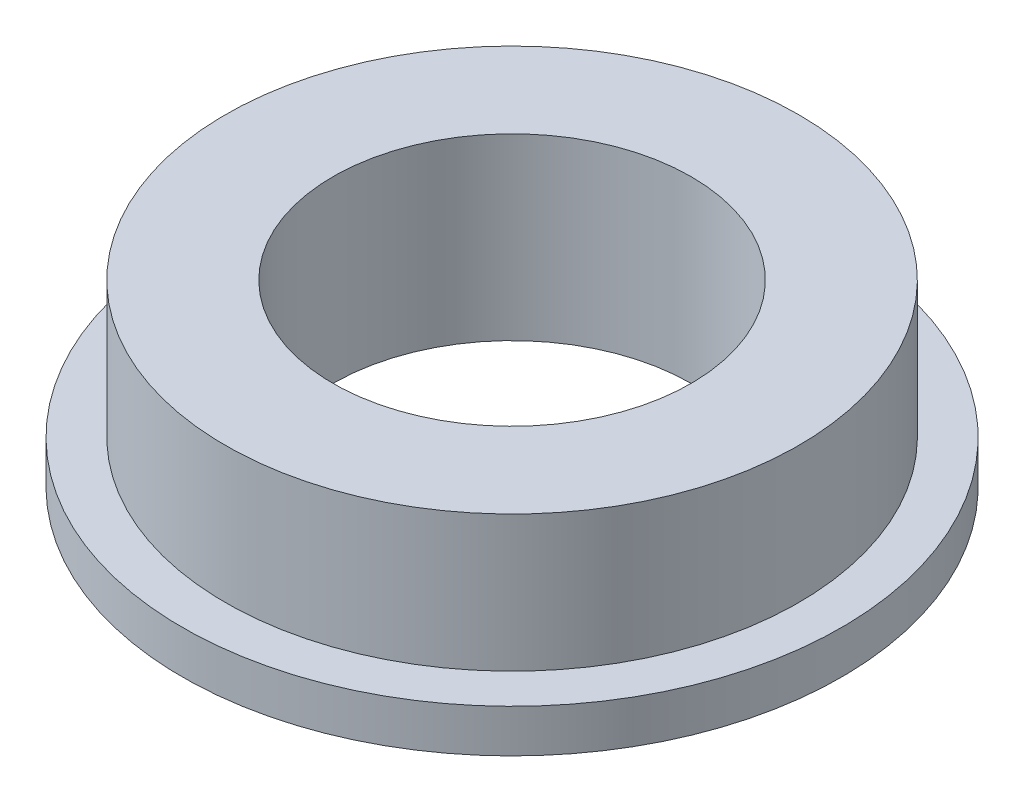
SolidWorks part; units mm, degrees
ref_plane "Front Plane" through (0, 0, 0) normal (0, 0, 1) x (1, 0, 0)
ref_plane "Top Plane" through (0, 0, 0) normal (0, 1, 0) x (1, 0, 0)
ref_plane "Right Plane" through (0, 0, 0) normal (1, 0, 0) x (0, 0, -1)
sketch "Sketch1" plane through (0, 0, 0) normal (0, 0, 1) x (1, 0, 0)
  line L0 (2.5, 0) -> (2.5, 2.5)
  line L1 (2.5, 2.5) -> (4, 2.5)
  line L2 (4, 2.5) -> (4, 0.6)
  line L3 (4, 0.6) -> (4.6, 0.6)
  line L4 (4.6, 0.6) -> (4.6, 0)
  line L5 (4.6, 0) -> (2.5, 0)
  line L6 (0, 0) -> (0, 2.5) construction
  dimension "D1" = 2.5
  dimension "D2" = 4
  dimension "D3" = 0.6
  dimension "D4" = 4.6
  dimension "D5" = 2.5
revolve "Revolve1" add sketch "Sketch1" angle 360 about L6
